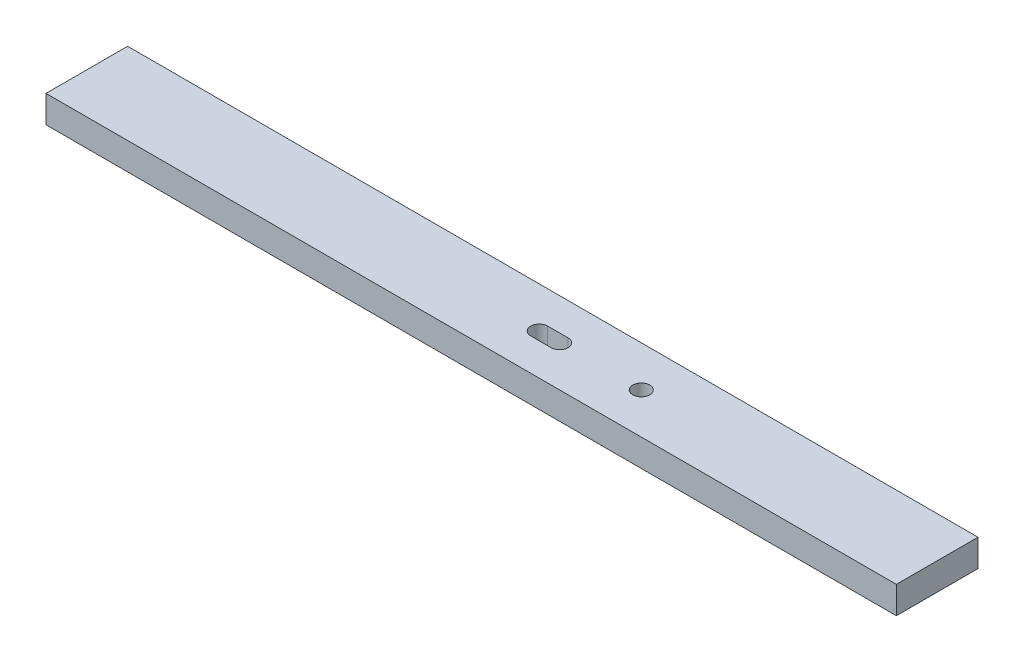
SolidWorks part; units mm, degrees
material "普通碳钢"
ref_plane "前视基准面" through (0, 0, 0) normal (0, 0, 1) x (1, 0, 0)
ref_plane "上视基准面" through (0, 0, 0) normal (0, 1, 0) x (1, 0, 0)
ref_plane "右视基准面" through (0, 0, 0) normal (1, 0, 0) x (0, 0, -1)
sketch "草图1" plane through (0, 0, 0) normal (1, 0, 0) x (0, 0, -1)
  line L1 (-12, -4) -> (12, -4)
  line L2 (-12, -4) -> (-12, 4)
  line L3 (-12, 4) -> (12, 4)
  line L4 (12, -4) -> (12, 4)
  line L5 (-12, -4) -> (12, 4) construction
  line L6 (-12, 4) -> (12, -4) construction
  point P0 (0, 0)
  dimension "D1" = 24
  dimension "D2" = 8
extrude "凸台-拉伸1" add sketch "草图1" along normal blind 250
sketch "草图2" plane through (0, 0, 0) normal (0, 1, 0) x (1, 0, 0)
  line L0 (250, 12) -> (250, -12) construction
  line L5 (133, 0) -> (139, 0) construction
  line L6 (133, 2.5) -> (139, 2.5)
  line L7 (133, -2.5) -> (139, -2.5)
  circle A4 centre (163, 0) radius 2.5
  arc A5 (133, 2.5) -> (133, -2.5) centre (133, 0) ccw
  arc A6 (139, -2.5) -> (139, 2.5) centre (139, 0) ccw
  point P6 (136, 0)
  point P13 (0, 0)
  dimension "D2" = 5
  dimension "D6" = 2.5
  dimension "D1" = 87
  dimension "D3" = 163
  dimension "D4" = 30
  dimension "D5" = 6
extrude "切除-拉伸3" cut sketch "草图2" against normal through all both and the other way through all
